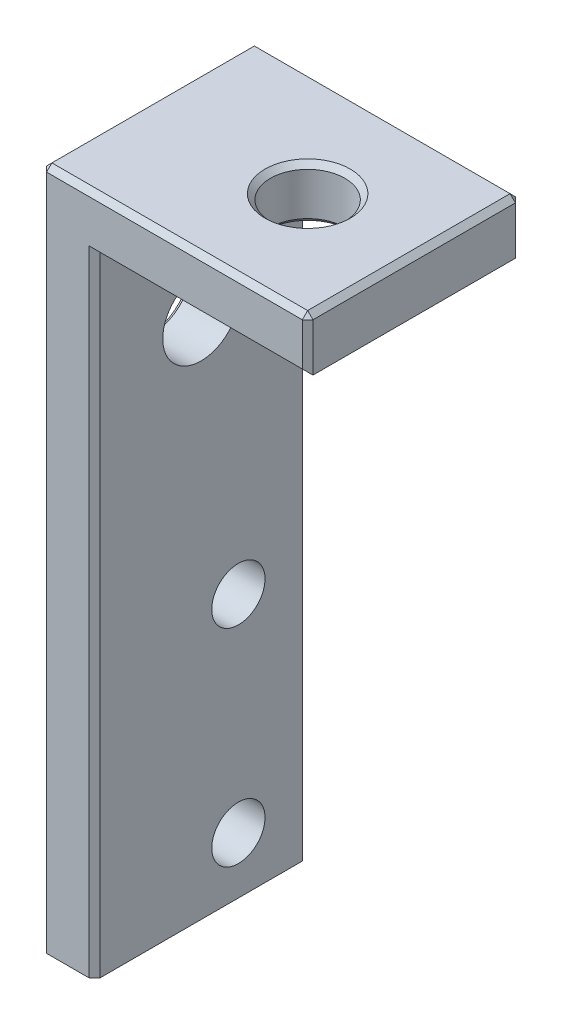
SolidWorks part; units mm, degrees
ref_plane "Front Plane" through (0, 0, 0) normal (0, 0, 1) x (1, 0, 0)
ref_plane "Top Plane" through (0, 0, 0) normal (0, 1, 0) x (1, 0, 0)
ref_plane "Right Plane" through (0, 0, 0) normal (1, 0, 0) x (0, 0, -1)
sketch "Sketch1" plane through (0, 0, 0) normal (0, 0, 1) x (1, 0, 0)
  line L0 (0, 39.5625) -> (0, -32.0625) construction
  line L1 (-37.375, 0) -> (58.375, 0) construction
  line L2 (0, 0) -> (0, 36.5)
  line L3 (0, 36.5) -> (12.5, 36.5)
  line L4 (12.5, 36.5) -> (12.5, 34)
  line L5 (12.5, 34) -> (2.5, 34)
  line L6 (2.5, 34) -> (2.5, 0)
  line L7 (2.5, 0) -> (0, 0)
  dimension "D1" = 2.5
  dimension "D2" = 2.5
  dimension "D3" = 10
  dimension "D4" = 34
extrude "Boss-Extrude1" add sketch "Sketch1" along normal blind 10
sketch "Sketch2" plane through (0, 34, 0) normal (0, -1, 0) x (1, 0, 0)
  circle A0 centre (7.5, 5) radius 1.75
  dimension "D1" = 3.5
  dimension "D3" = 7.5
  dimension "D2" = 5
extrude "Cut-Extrude1" cut sketch "Sketch2" against normal blind 10
sketch "Sketch3" plane through (2.5, 0, 0) normal (1, 0, 0) x (0, 0, -1)
  line L0 (-5, 39.5141) -> (-5, -3.4018) construction
  line L1 (-21.2213, 12) -> (22.3467, 12) construction
  line L2 (0, 0) -> (0, 34) construction
  line L4 (-10, 34) -> (0, 34) construction
  circle A0 centre (-3.25, 7.15) radius 1.25
  circle A1 centre (-3.25, 16.85) radius 1.25
  circle A3 centre (-5, 29) radius 1.8
  dimension "D3" = 2.5
  dimension "D5" = 3.25
  dimension "D6" = 3.6
  dimension "D7" = 5
  dimension "D1" = 5
  dimension "D2" = 12
  dimension "D4" = 4.85
extrude "Cut-Extrude2" cut sketch "Sketch3" against normal through all
chamfer "Chamfer1" distance 0.25 21 edges at (7.5, 36.5, 3.25) (0, 0, 5) (2.5, 0, 5) (0, 18.25, 10) (1.25, 0, 10) (2.5, 17, 10) (7.5, 34, 10) (12.5, 35.25, 10) (12.5, 36.5, 5) (6.25, 36.5, 10) (0, 36.5, 5) (2.5, 17, 0) (7.5, 34, 0) (12.5, 35.25, 0) (6.25, 36.5, 0) (0, 18.25, 0) (1.25, 0, 0) (9.25, 34, 5) (0, 8.4, 3.25) (0, 15.6, 3.25) (0, 30.8, 5)
sketch "Sketch4" plane through (2.5, 0, 0) normal (1, 0, 0) x (0, 0, -1)
  line L1 (0, 0) -> (-13.0225, 0)
  line L2 (0, 0) -> (0, 4.5)
  line L3 (0, 4.5) -> (-13.0225, 4.5)
  line L4 (-13.0225, 0) -> (-13.0225, 4.5)
  dimension "D1" = 4.5
extrude "Cut-Extrude3" cut sketch "Sketch4" against normal through all
